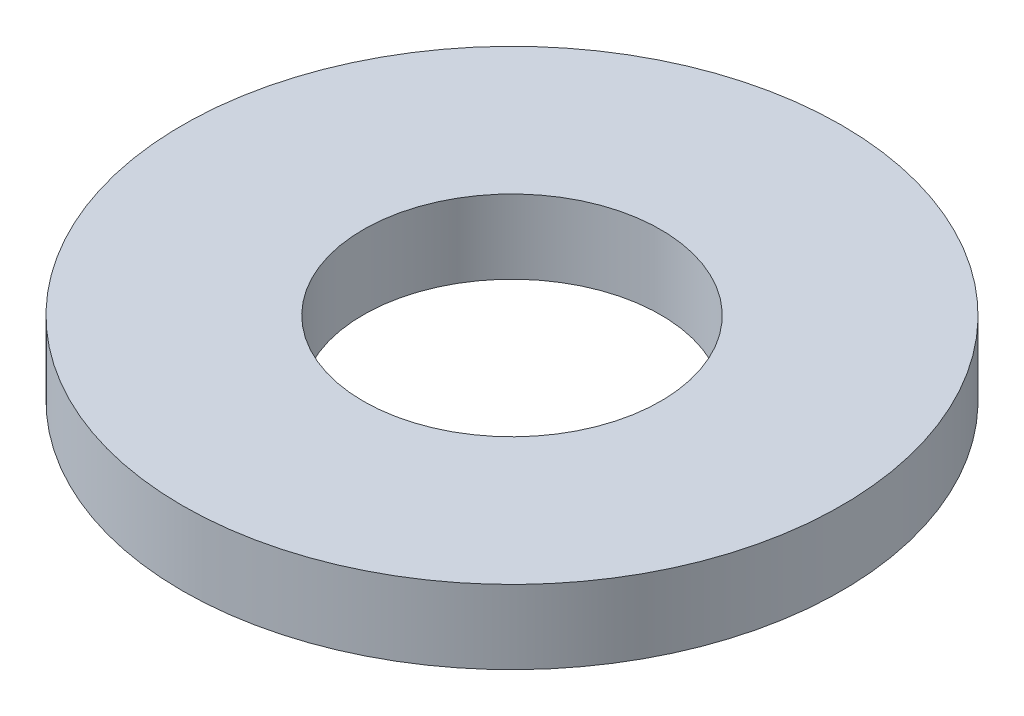
SolidWorks part; units mm, degrees
ref_plane "Front Plane" through (0, 0, 0) normal (0, 0, 1) x (1, 0, 0)
ref_plane "Top Plane" through (0, 0, 0) normal (0, 1, 0) x (1, 0, 0)
ref_plane "Right Plane" through (0, 0, 0) normal (1, 0, 0) x (0, 0, -1)
sketch "Sketch1" plane through (0, 0, 0) normal (0, 1, 0) x (1, 0, 0)
  circle A0 centre (0, 0) radius 7.9375
  dimension "OD" = 15.875
extrude "Boss-Extrude1" add sketch "Sketch1" along normal blind 1.778
sketch "Sketch5" plane through (0, 1.778, 0) normal (0, 1, 0) x (-1, 0, 0)
  circle A0 centre (0, 0) radius 3.5814
  dimension "ID" = 7.1628
extrude "Cut-Extrude1" cut sketch "Sketch5" against normal through all
